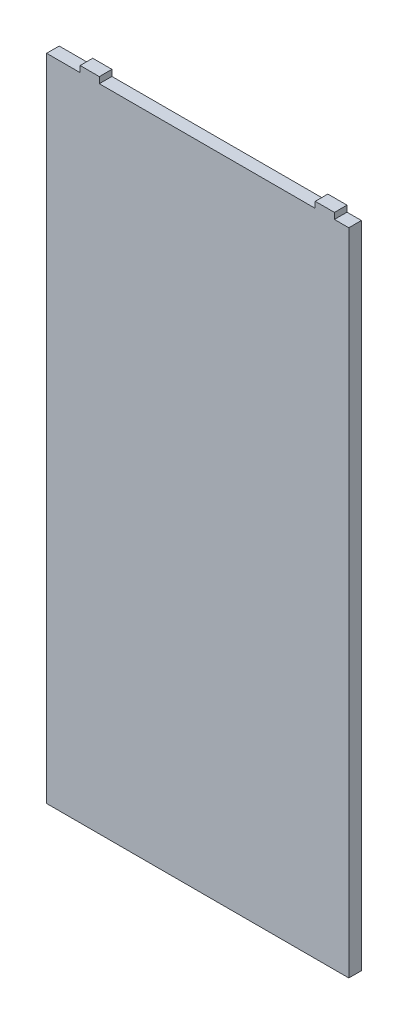
SolidWorks part; units mm, degrees
ref_plane "Front Plane" through (0, 0, 0) normal (0, 0, 1) x (1, 0, 0)
ref_plane "Top Plane" through (0, 0, 0) normal (0, 1, 0) x (1, 0, 0)
ref_plane "Right Plane" through (0, 0, 0) normal (1, 0, 0) x (0, 0, -1)
sketch "Sketch1" plane through (0, 0, 0) normal (0, 0, 1) x (1, 0, 0)
  line L0 (11.9857, -26.5471) -> (11.9857, 25.0529)
  line L1 (-12.0143, -26.5471) -> (11.9857, -26.5471)
  line L2 (-12.0143, 25.0529) -> (-12.0143, -26.5471)
  line L3 (11.9857, 25.0529) -> (-12.0143, 25.0529)
extrude "Boss-Extrude1" add sketch "Sketch1" along normal blind 1
sketch "Sketch2" plane through (0, 0, 0) normal (0, 0, -1) x (-1, 0, 0)
  line L12 (-10.8438, 25.5383) -> (-9.3192, 25.5383)
  line L13 (-10.8438, 25.5383) -> (-10.8438, 24.8504)
  line L14 (-10.8438, 24.8504) -> (-9.3192, 24.8504)
  line L15 (-9.3192, 24.8504) -> (-9.3192, 25.5383)
  line L16 (7.8278, 24.8551) -> (7.8278, 25.5429)
  line L17 (7.8278, 24.8551) -> (9.3523, 24.8551)
  line L18 (9.3523, 24.8551) -> (9.3523, 25.5429)
  line L19 (7.8278, 25.5429) -> (9.3523, 25.5429)
extrude "Boss-Extrude2" add sketch "Sketch2" against normal blind 1
sketch "Sketch3" plane through (0, 0, 0) normal (0, 0, -1) x (-1, 0, 0)
  arc A0 (3.5439, -26.5859) -> (-3.3831, -26.5928) centre (0.0804, -26.5563) ccw
  line M8 (-11.9857, -26.5471) -> (12.0143, -26.5471)
extrude "Cut-Extrude1" cut sketch "Sketch3" against normal blind 0.5 and the other way through all contours A0 M8
